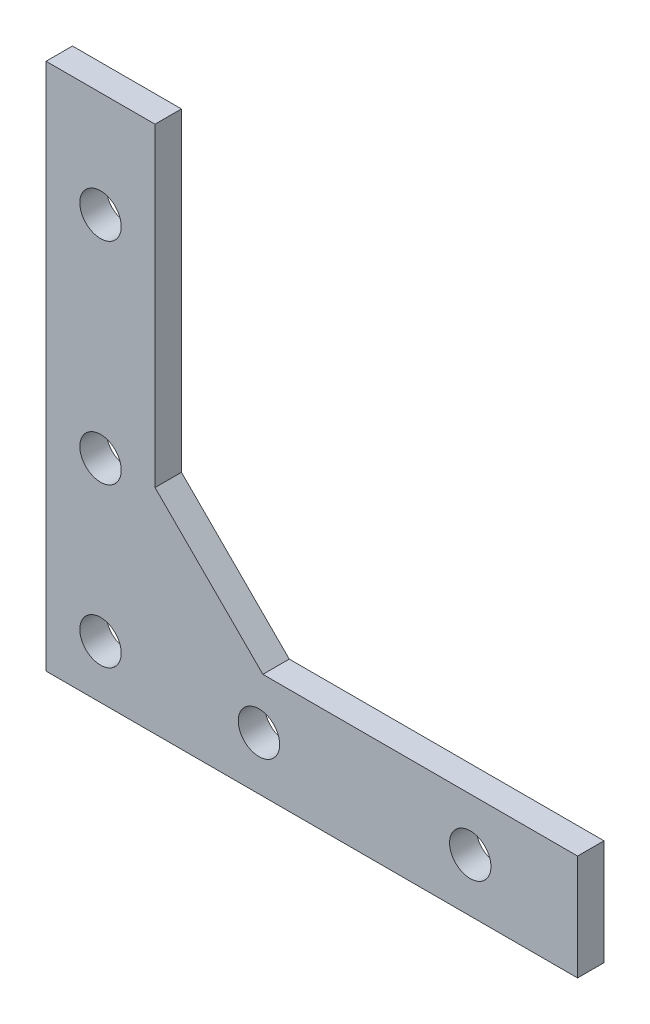
SolidWorks part; units mm, degrees
ref_plane "Front Plane" through (0, 0, 0) normal (0, 0, 1) x (1, 0, 0)
ref_plane "Top Plane" through (0, 0, 0) normal (0, 1, 0) x (1, 0, 0)
ref_plane "Right Plane" through (0, 0, 0) normal (1, 0, 0) x (0, 0, -1)
sketch "Sketch1" plane through (0, 0, 0) normal (0, 0, 1) x (1, 0, 0)
  line L0 (-254, 0) -> (-267.1034, 0)
  line L1 (-267.1034, 0) -> (-267.1034, 63.5)
  line L2 (-267.1034, 63.5) -> (-254, 63.5)
  line L3 (-254, -16.7024) -> (-254, 609.6) construction
  line L4 (-254, 0) -> (-203.2, 0)
  line L6 (-203.2, 0) -> (-203.2, 12.7)
  line L7 (-254, 12.7) -> (254, 12.7) construction
  line L8 (-203.2, 12.7) -> (-241.034, 12.7)
  line L9 (-241.034, 12.7) -> (-254, 25.666)
  line L10 (-254, 25.666) -> (-254, 63.5)
  dimension "D1" = 63.5
  dimension "D2" = 12.7
extrude "Boss-Extrude1" add sketch "Sketch1" along normal blind 3.175
sketch "Sketch2" plane through (0, 0, 3.175) normal (0, 0, 1) x (1, 0, 0)
  line L0 (-260.5517, 63.5) -> (-260.5517, 50.8) construction
  line L1 (-254, 63.5) -> (-267.1034, 63.5) construction
  line L2 (-260.5517, 50.8) -> (-260.5517, 25.4382) construction
  line L3 (-260.5517, 6.3882) -> (-241.5017, 6.3882) construction
  line L4 (-260.5517, 25.4382) -> (-260.5517, 6.3882) construction
  line L5 (-241.5017, 6.3882) -> (-216.1017, 6.3882) construction
  line L6 (-203.2, 6.35) -> (-216.1017, 6.3882) construction
  line L7 (-203.2, 0) -> (-203.2, 12.7) construction
  dimension "D1" = 19.05
  dimension "D2" = 19.05
hole_wizard "#10 Clearance Hole1" positions "Sketch3" profile "Sketch4" hole size "#10" standard "ANSI Inch" end condition through all
sketch "Sketch3" plane through (0, 0, 3.175) normal (0, 0, 1) x (1, 0, 0)
  point P0 (-260.5517, 6.3882)
  point P3 (-260.5517, 25.4382)
  point P6 (-260.5517, 50.8)
  point P9 (-241.5017, 6.3882)
  point P12 (-216.1017, 6.3882)
sketch "Sketch4" plane through (-260.5517, 6.3882, 3.175) normal (1, 0, 0) x (0, -1, 0)
  line L0 (0, 0) -> (0, 3.175)
  line L1 (0, 3.175) -> (2.4892, 3.175)
  line L2 (2.4892, 3.175) -> (2.4892, 0)
  line L5 (2.4892, 0) -> (0, 0)
  line L11 (0, -6.35) -> (0, 107.95) construction
  dimension "Thru Hole Dia." = 4.9784
  dimension "Thru Hole Depth" = 3.175
